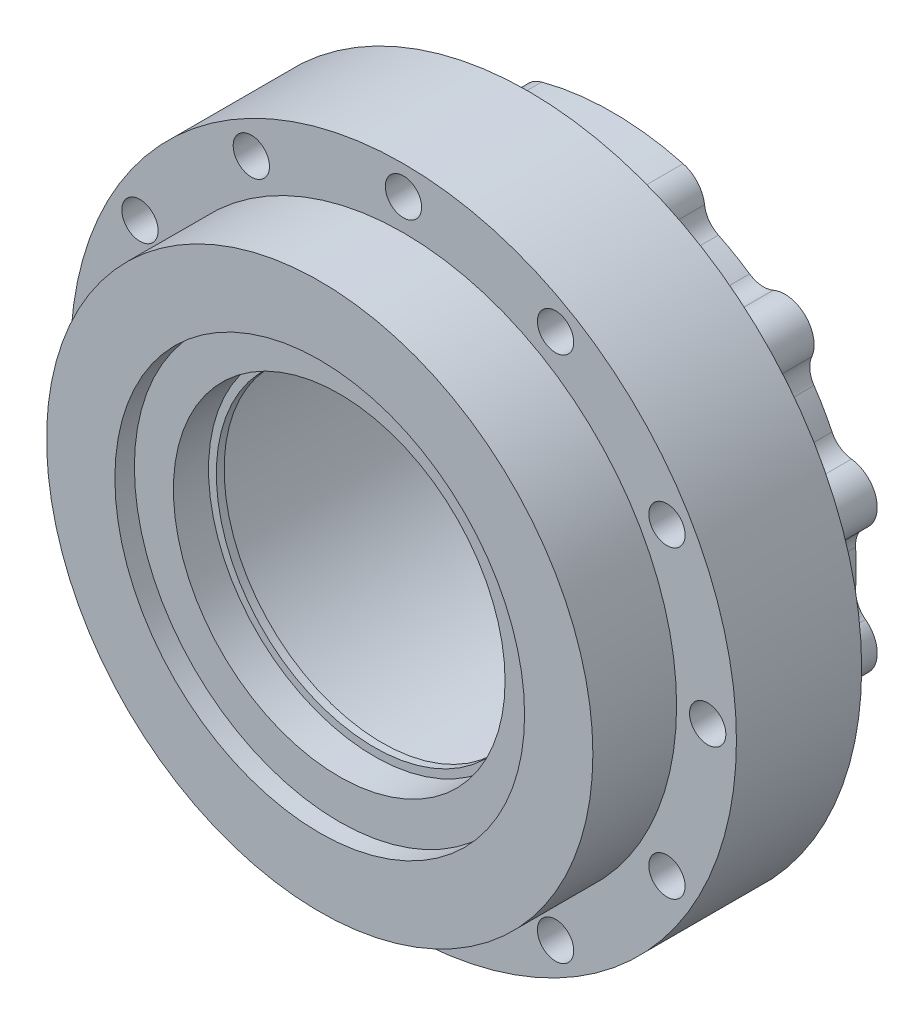
SolidWorks part; units mm, degrees
material "6061-T6 (SS)"
ref_plane "Front Plane" through (0, 0, 0) normal (0, 0, 1) x (1, 0, 0)
ref_plane "Top Plane" through (0, 0, 0) normal (0, 1, 0) x (1, 0, 0)
ref_plane "Right Plane" through (0, 0, 0) normal (1, 0, 0) x (0, 0, -1)
sketch "Sketch1" plane through (0, 0, 0) normal (1, 0, 0) x (0, 0, -1)
  line L0 (-84.7958, 52.5) -> (-79.7958, 52.5)
  line L2 (-68.7958, 40.5) -> (-70.7958, 40.5)
  line L4 (-84.7958, 52.5) -> (-84.7958, 70)
  line L5 (-84.7958, 70) -> (-9.7958, 70)
  line L7 (-79.7958, 52.5) -> (-79.7958, 42.5)
  line L11 (-68.7958, 40.5) -> (-68.7958, 55)
  line L12 (-68.7958, 55) -> (-9.7958, 55)
  line L13 (-70.7958, 40.5) -> (-70.7958, 42.5)
  line L14 (-9.7958, 70) -> (-9.7958, 55)
  line L18 (-163.8227, 0) -> (139.4858, 0) construction
  line L19 (-70.7958, 42.5) -> (-79.7958, 42.5)
  dimension "D3" = 75
  dimension "D5" = 9
  dimension "D6" = 2
  dimension "D7" = 5
  dimension "D8" = 2
revolve "Revolve1" add sketch "Sketch1" angle 360 about L18
sketch "Sketch2" plane through (0, 0, 9.7958) normal (0, 0, -1) x (-1, 0, 0)
  line L0 (0, 62.5) -> (0, -62.5) construction
  circle A0 centre (0, 0) radius 62.5 construction
  circle A1 centre (0, 62.5) radius 4
  circle A2 centre (0, -62.5) radius 4
  dimension "D1" = 125
  dimension "D2" = 8
extrude "Cut-Extrude1" cut sketch "Sketch2" against normal blind 10
sketch "Sketch5" plane through (0, 0, 9.7958) normal (0, 0, 1) x (1, 0, 0)
  line L0 (0, 70) -> (0, -70) construction
  line L3 (-44.1942, 44.1942) -> (0, 0) construction
  line L8 (-16.1762, 60.3704) -> (0, 0) construction
  line L9 (16.1762, 60.3704) -> (0, 0) construction
  line L10 (44.1942, 44.1942) -> (0, 0) construction
  line L11 (60.3704, 16.1762) -> (0, 0) construction
  line L12 (60.3704, -16.1762) -> (0, 0) construction
  line L13 (44.1942, -44.1942) -> (0, 0) construction
  line L14 (16.1762, -60.3704) -> (0, 0) construction
  line L19 (-16.1762, -60.3704) -> (0, 0) construction
  line L20 (-44.1942, -44.1942) -> (0, 0) construction
  line L21 (-60.3704, -16.1762) -> (0, 0) construction
  line L22 (-60.3704, 16.1762) -> (0, 0) construction
  circle A0 centre (0, 0) radius 62.5 construction
  point P12 (-44.1942, 44.1942)
  point P14 (-62.5, 0)
  point P15 (44.1942, 44.1942)
  point P17 (62.5, 0)
  point P23 (-16.1762, 60.3704)
  point P24 (16.1762, 60.3704)
  point P26 (60.3704, 16.1762)
  point P27 (60.3704, -16.1762)
  point P28 (44.1942, -44.1942)
  point P29 (16.1762, -60.3704)
  point P30 (-16.1762, -60.3704)
  point P31 (-44.1942, -44.1942)
  point P32 (-60.3704, -16.1762)
  point P33 (-60.3704, 16.1762)
  dimension "D1" = 125
  dimension "D3" = 12
  dimension "D2" = 45
hole_wizard "M10x1.25 Tapped Hole1" positions "Sketch5" profile "Sketch6" tap size "M10x1.25" standard "ANSI Metric"
sketch "Sketch6" plane through (-60.3704, 16.1762, 9.7958) normal (1, 0, 0) x (0, 1, 0)
  line L0 (0, 0) -> (0, 16.6438)
  line L1 (0, 16.6438) -> (4.4, 14)
  line L2 (4.4, 14) -> (4.4, 0)
  line L5 (4.4, 0) -> (0, 0)
  line L10 (0, 16.6438) -> (-4.4, 14) construction
  line L11 (0, -6.35) -> (0, 107.95) construction
  dimension "Tap Drill Dia." = 8.8
  dimension "Tap Drill Depth" = 14
  dimension "Drill Angle" = 118
cosmetic thread "Hole Thread1" parameters "D1"=12, "D2"=10
cosmetic thread "Hole Thread2" parameters "D1"=12, "D2"=10
cosmetic thread "Hole Thread3" parameters "D1"=12, "D2"=10
cosmetic thread "Hole Thread4" parameters "D1"=12, "D2"=10
cosmetic thread "Hole Thread5" parameters "D1"=12, "D2"=10
cosmetic thread "Hole Thread7" parameters "D1"=12, "D2"=10
cosmetic thread "Hole Thread8" parameters "D1"=12, "D2"=10
cosmetic thread "Hole Thread9" parameters "D1"=12, "D2"=10
cosmetic thread "Hole Thread10" parameters "D1"=12, "D2"=10
cosmetic thread "Hole Thread12" parameters "D1"=12, "D2"=10
cosmetic thread "Hole Thread13" parameters "D1"=12, "D2"=10
cosmetic thread "Hole Thread14" parameters "D1"=12, "D2"=10
sketch "Sketch7" plane through (0, 0, 0) normal (1, 0, 0) x (0, 0, -1)
  line L0 (-31.2502, 70) -> (-63.3413, 70)
  line L1 (-84.7958, 70) -> (-9.7958, 70) construction
  line L2 (-63.3413, 70) -> (-63.3413, 85.3347)
  line L3 (-63.3413, 85.3347) -> (-31.2502, 85.3347)
  line L4 (-31.2502, 85.3347) -> (-31.2502, 70)
  point P5 (-47.2958, 70)
revolve "Revolve2" add sketch "Sketch7" angle 360 about L18
sketch "Sketch8" plane through (0, 0, 31.2502) normal (0, 0, -1) x (-1, 0, 0)
  circle A0 centre (0, 77.9691) radius 4.6522
  circle A1 centre (38.9846, 67.5233) radius 4.6522
  circle A2 centre (67.5233, 38.9846) radius 4.6522
  circle A3 centre (77.9691, 0) radius 4.6522
  circle A4 centre (67.5233, -38.9846) radius 4.6522
  circle A5 centre (38.9846, -67.5233) radius 4.6522
  circle A6 centre (0, -77.9691) radius 4.6522
  circle A7 centre (-38.9846, -67.5233) radius 4.6522
  circle A8 centre (-67.5233, -38.9846) radius 4.6522
  circle A9 centre (-77.9691, 0) radius 4.6522
  circle A10 centre (-67.5233, 38.9846) radius 4.6522
  circle A11 centre (-38.9846, 67.5233) radius 4.6522
  circle A12 centre (0, 0) radius 85.3347 construction
  point P29 (0, 0)
  dimension "D1" = 12
extrude "Cut-Extrude2" cut sketch "Sketch8" against normal through all
sketch "Sketch9" plane through (0, 0, 9.7958) normal (0, 0, -1) x (-1, 0, 0)
  arc A0 (-38.5822, 49.1697) -> (-49.1697, 38.5822) centre (-44.1942, 44.1942) ccw
  arc A2 (-8.8283, 61.8733) -> (-23.2911, 57.9981) centre (-16.1762, 60.3704) ccw
  arc A3 (23.2911, 57.9981) -> (8.8283, 61.8733) centre (16.1762, 60.3704) ccw
  arc A4 (49.1697, 38.5822) -> (38.5822, 49.1697) centre (44.1942, 44.1942) ccw
  arc A5 (61.8733, 8.8283) -> (57.9981, 23.2911) centre (60.3704, 16.1762) ccw
  arc A6 (57.9981, -23.2911) -> (61.8733, -8.8283) centre (60.3704, -16.1762) ccw
  arc A7 (38.5822, -49.1697) -> (49.1697, -38.5822) centre (44.1942, -44.1942) ccw
  arc A8 (8.8283, -61.8733) -> (23.2911, -57.9981) centre (16.1762, -60.3704) ccw
  arc A9 (-23.2911, -57.9981) -> (-8.8283, -61.8733) centre (-16.1762, -60.3704) ccw
  arc A10 (-49.1697, -38.5822) -> (-38.5822, -49.1697) centre (-44.1942, -44.1942) ccw
  arc A11 (-61.8733, -8.8283) -> (-57.9981, -23.2911) centre (-60.3704, -16.1762) ccw
  arc A12 (-57.9981, 23.2911) -> (-61.8733, 8.8283) centre (-60.3704, 16.1762) ccw
  arc A13 (-23.2911, 57.9981) -> (-38.5822, 49.1697) centre (0, 0) ccw
  arc A14 (8.8283, 61.8733) -> (-8.8283, 61.8733) centre (0, 0) ccw
  arc A15 (38.5822, 49.1697) -> (23.2911, 57.9981) centre (0, 0) ccw
  arc A16 (57.9981, 23.2911) -> (49.1697, 38.5822) centre (0, 0) ccw
  arc A17 (61.8733, -8.8283) -> (61.8733, 8.8283) centre (0, 0) ccw
  arc A18 (49.1697, -38.5822) -> (57.9981, -23.2911) centre (0, 0) ccw
  arc A19 (23.2911, -57.9981) -> (38.5822, -49.1697) centre (0, 0) ccw
  arc A20 (-8.8283, -61.8733) -> (8.8283, -61.8733) centre (0, 0) ccw
  arc A21 (-38.5822, -49.1697) -> (-23.2911, -57.9981) centre (0, 0) ccw
  arc A22 (-57.9981, -23.2911) -> (-49.1697, -38.5822) centre (0, 0) ccw
  arc A23 (-61.8733, 8.8283) -> (-61.8733, -8.8283) centre (0, 0) ccw
  arc A24 (-49.1697, 38.5822) -> (-57.9981, 23.2911) centre (0, 0) ccw
  circle A27 centre (0, 0) radius 70
  point P29 (0, 0)
  circle M39 centre (0, 0) radius 70
  dimension "D1" = 15
  dimension "D2" = 12
extrude "Cut-Extrude4" cut sketch "Sketch9" against normal up to surface (21.4544 mm away) contours A13 A2 A0 M39 | A15 A4 A3 M39 | A24 A0 A12 M39 | A23 A12 A11 M39 | A16 A5 A4 M39 | A17 A6 A5 M39 | A18 A7 A6 M39 | A19 A8 A7 M39 | A21 A10 A9 M39 | A22 A11 A10 M39 up to face at (-4.6522, 77.9691, 31.2502)
fillet "Fillet1" radius 6.35 20 edges at (49.1697, 38.5822, 20.523) (23.2911, 57.9981, 20.523) (-38.5822, 49.1697, 20.523) (-49.1697, 38.5822, 20.523) (-23.2911, 57.9981, 20.523) (-57.9981, 23.2911, 20.523) (-61.8733, 8.8283, 20.523) (-61.8733, -8.8283, 20.523) (-57.9981, -23.2911, 20.523) (-49.1697, -38.5822, 20.523) (-38.5822, -49.1697, 20.523) (-23.2911, -57.9981, 20.523) (23.2911, -57.9981, 20.523) (38.5822, -49.1697, 20.523) (49.1697, -38.5822, 20.523) (57.9981, -23.2911, 20.523) (61.8733, -8.8283, 20.523) (61.8733, 8.8283, 20.523) (57.9981, 23.2911, 20.523) (38.5822, 49.1697, 20.523)
chamfer "Chamfer1" distance 0.5 angle 45 12 edges at (-20.5762, -60.3704, 9.7958) (-48.5942, -44.1942, 9.7958) (-64.7704, -16.1762, 9.7958) (11.7762, -60.3704, 9.7958) (39.7942, -44.1942, 9.7958) (55.9704, -16.1762, 9.7958) (55.9704, 16.1762, 9.7958) (39.7942, 44.1942, 9.7958) (11.7762, 60.3704, 9.7958) (-20.5762, 60.3704, 9.7958) (-48.5942, 44.1942, 9.7958) (-64.7704, 16.1762, 9.7958)
